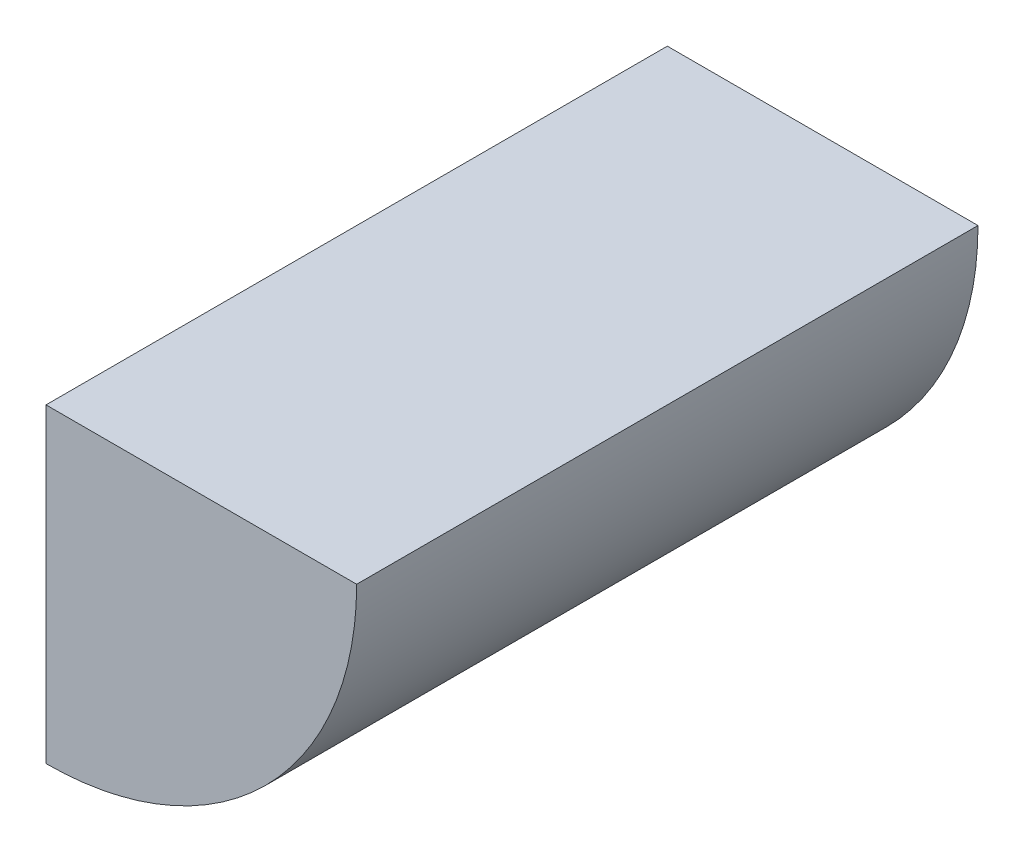
SolidWorks part; units mm, degrees
ref_plane "Alzado" through (0, 0, 0) normal (0, 0, 1) x (1, 0, 0)
ref_plane "Planta" through (0, 0, 0) normal (0, 1, 0) x (1, 0, 0)
ref_plane "Vista lateral" through (0, 0, 0) normal (1, 0, 0) x (0, 0, -1)
sketch "Croquis2" plane through (0, 0, 0) normal (0, 0, 1) x (1, 0, 0)
  line L0 (0, 0) -> (0, -25)
  line L1 (0, 0) -> (25, 0)
  arc A0 (0, -25) -> (25, 0) centre (0, 0) ccw
  dimension "D1" = 50
extrude "Saliente-Extruir1" add sketch "Croquis2" along normal blind 50
sketch "Croquis3" plane through (0, 0, 0) normal (0, 0, -1) x (-1, 0, 0)
  circle A0 centre (-10.1263, -9.9765) radius 5
  dimension "D1" = 10
extrude "Cortar-Extruir1" cut sketch "Croquis3" against normal blind 10
